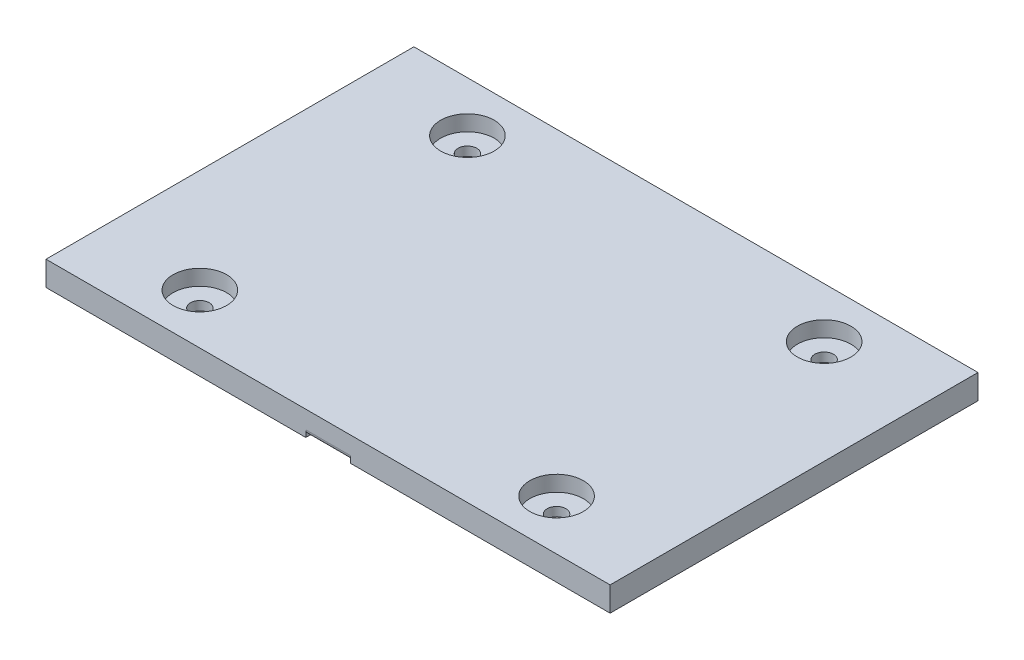
SolidWorks part; units mm, degrees
ref_plane "Спереди" through (0, 0, 0) normal (0, 0, 1) x (1, 0, 0)
ref_plane "Сверху" through (0, 0, 0) normal (0, 1, 0) x (1, 0, 0)
ref_plane "Справа" through (0, 0, 0) normal (1, 0, 0) x (0, 0, -1)
ref_plane "Плоскость4" through (0, 60.646, 0) normal (0, -1, 0) x (-1, 0, 0)
sketch "Эскиз1" plane through (0, 60.646, 0) normal (0, -1, 0) x (-1, 0, 0)
  line L0 (-128.059, -48.2731) -> (-128.059, -130.7731)
  line L1 (-128.059, -130.7731) -> (-1.559, -130.7731)
  line L2 (-1.559, -130.7731) -> (-1.559, -48.2731)
  line L3 (-1.559, -48.2731) -> (-128.059, -48.2731)
  circle A0 centre (-24.809, -59.5231) radius 2.1
  circle A1 centre (-104.809, -59.5231) radius 2.1
  circle A2 centre (-24.809, -119.5231) radius 2.1
  circle A3 centre (-104.809, -119.5231) radius 2.1
extrude "Бобышка-Вытянуть1" add sketch "Эскиз1" along normal blind 2
ref_plane "Плоскость5" through (0, 58.646, 0) normal (0, -1, 0) x (-1, 0, 0)
sketch "Эскиз3" plane through (0, 58.646, 0) normal (0, -1, 0) x (-1, 0, 0)
  line L1 (-32.809, -57.5231) -> (-32.809, -84.5231)
  line L6 (-59.809, -57.5231) -> (-59.809, -48.2731)
  line L7 (-1.559, -48.2731) -> (-128.059, -48.2731) construction
  line L9 (-69.809, -57.5231) -> (-69.809, -48.2731)
  line L10 (-69.809, -48.2731) -> (-59.809, -48.2731)
  line L11 (-69.809, -121.5231) -> (-69.809, -130.7731)
  line L12 (-128.059, -130.7731) -> (-1.559, -130.7731) construction
  line L13 (-69.809, -130.7731) -> (-59.809, -130.7731)
  line L14 (-59.809, -130.7731) -> (-59.809, -121.5231)
  line L15 (-96.809, -121.5231) -> (-96.809, -94.5231)
  line L16 (-96.809, -84.5231) -> (-116.809, -84.5231)
  line L17 (-116.809, -84.5231) -> (-116.809, -94.5231)
  line L18 (-116.809, -94.5231) -> (-96.809, -94.5231)
  line L19 (-32.809, -94.5231) -> (-32.809, -121.5231)
  line L20 (-32.809, -94.5231) -> (-12.809, -94.5231)
  line L21 (-12.809, -94.5231) -> (-12.809, -84.5231)
  line L22 (-12.809, -84.5231) -> (-32.809, -84.5231)
  line L23 (-32.809, -121.5231) -> (-59.809, -121.5231)
  line L24 (-59.809, -130.7731) -> (-69.809, -130.7731)
  line L25 (-69.809, -121.5231) -> (-96.809, -121.5231)
  line L26 (-96.809, -84.5231) -> (-96.809, -57.5231)
  line L27 (-96.809, -57.5231) -> (-69.809, -57.5231)
  line L28 (-59.809, -57.5231) -> (-32.809, -57.5231)
extrude "Вырез-Вытянуть1" cut sketch "Эскиз3" against normal blind 0.5 contours L28 L6 L10 L9 L27 L26 L16 L17 L18 L15 L25 L11 L13 L14 L23 L19 L20 L21 L22 L1
fillet "Скругление1" radius 1 2 edges at (64.809, 59.146, 48.2731) (64.809, 59.146, 130.7731)
sketch "Эскиз4" plane through (0, 60.646, 0) normal (0, -1, 0) x (-1, 0, 0)
  line L0 (-1.559, -48.2731) -> (-1.559, -130.7731)
  line L1 (-1.559, -130.7731) -> (-128.059, -130.7731)
  line L2 (-128.059, -130.7731) -> (-128.059, -48.2731)
  line L3 (-128.059, -48.2731) -> (-1.559, -48.2731)
  circle A0 centre (-24.809, -59.5231) radius 6
  circle A1 centre (-104.809, -59.5231) radius 6
  circle A2 centre (-104.809, -119.5231) radius 6
  circle A3 centre (-24.809, -119.5231) radius 6
extrude "Бобышка-Вытянуть3" add sketch "Эскиз4" against normal blind 3.5
